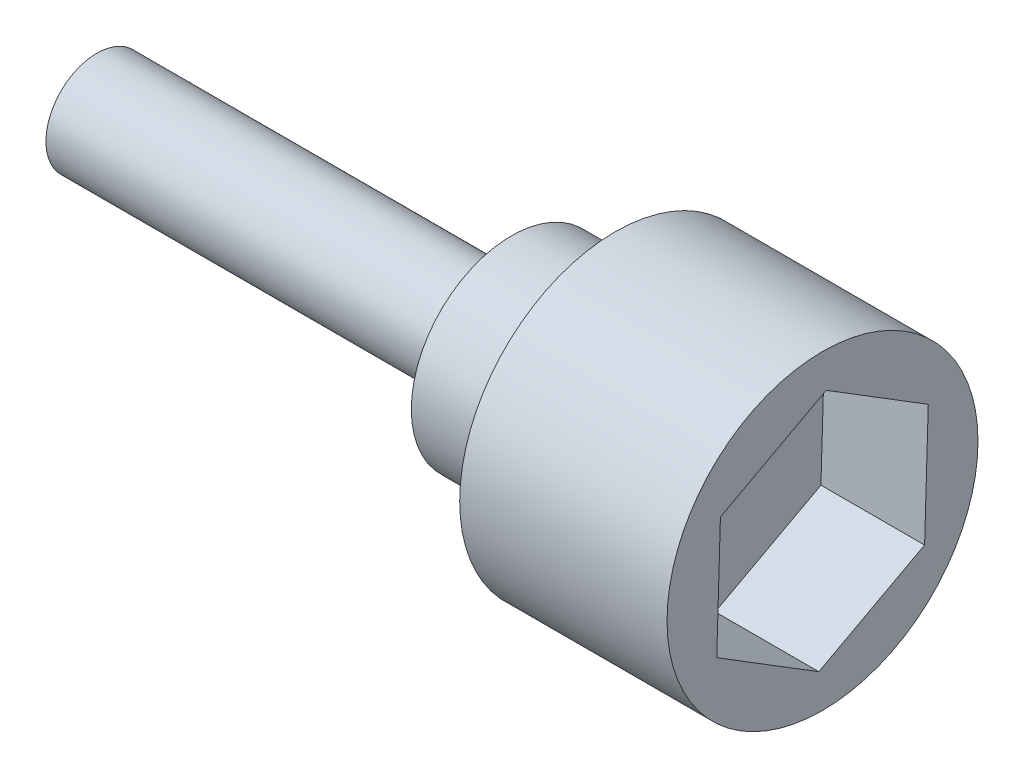
SolidWorks part; units mm, degrees
ref_plane "Front Plane" through (0, 0, 0) normal (0, 0, 1) x (1, 0, 0)
ref_plane "Top Plane" through (0, 0, 0) normal (0, 1, 0) x (1, 0, 0)
ref_plane "Right Plane" through (0, 0, 0) normal (1, 0, 0) x (0, 0, -1)
sketch "Sketch1" plane through (0, 0, 0) normal (1, 0, 0) x (0, 0, -1)
  circle A0 centre (0, 0) radius 0.9834
  dimension "D1" = 1.9668
extrude "Boss-Extrude1" add sketch "Sketch1" along normal blind 8
sketch "Sketch2" plane through (8, 0, 0) normal (1, 0, 0) x (0, 0, -1)
  circle A0 centre (0, 0) radius 1.9334
  dimension "D1" = 3.8668
extrude "Boss-Extrude2" add sketch "Sketch2" along normal blind 6
sketch "Sketch3" plane through (14, 0, 0) normal (1, 0, 0) x (0, 0, -1)
  circle A0 centre (0, 0) radius 3
  dimension "D1" = 6
extrude "Boss-Extrude3" add sketch "Sketch3" against normal blind 4
sketch "Sketch7" plane through (14, 0, 0) normal (1, 0, 0) x (0, 0, -1)
  line L1 (2.0407, 1.0962) -> (0.071, 2.3154)
  line L2 (0.071, 2.3154) -> (-1.9697, 1.2192)
  line L3 (-1.9697, 1.2192) -> (-2.0407, -1.0962)
  line L4 (-2.0407, -1.0962) -> (-0.071, -2.3154)
  line L5 (-0.071, -2.3154) -> (1.9697, -1.2192)
  line L6 (1.9697, -1.2192) -> (2.0407, 1.0962)
  circle A1 centre (0, 0) radius 2.0061 construction
extrude "Cut-Extrude1" cut sketch "Sketch7" against normal blind 2
